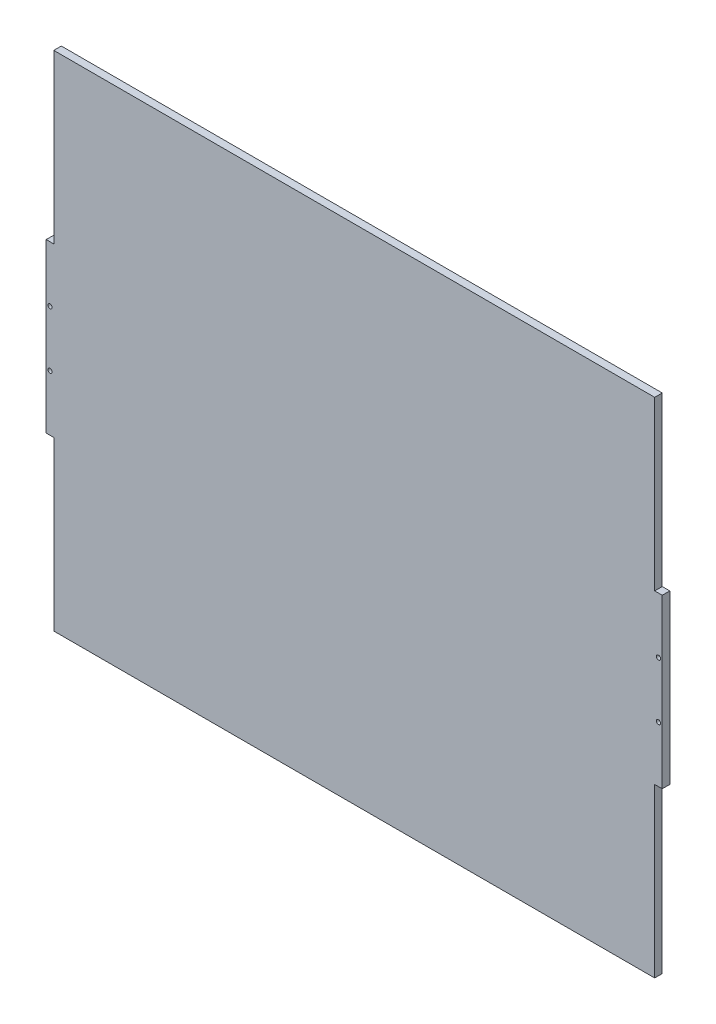
SolidWorks part; units mm, degrees
ref_plane "Front Plane" through (0, 0, 0) normal (0, 0, 1) x (1, 0, 0)
ref_plane "Top Plane" through (0, 0, 0) normal (0, 1, 0) x (1, 0, 0)
ref_plane "Right Plane" through (0, 0, 0) normal (1, 0, 0) x (0, 0, -1)
sketch "Sketch1" plane through (0, 0, 0) normal (0, 0, 1) x (1, 0, 0)
  line L1 (0, 0) -> (490, 0)
  line L2 (0, 0) -> (0, 400)
  line L3 (0, 400) -> (490, 400)
  line L4 (490, 0) -> (490, 400)
  dimension "D1" = 490
  dimension "D2" = 400
extrude "Boss-Extrude1" add sketch "Sketch1" along normal blind 6
sketch "Sketch2" plane through (0, 0, 6) normal (0, 0, 1) x (1, 0, 0)
  line L1 (490, 400) -> (484, 400)
  line L2 (490, 400) -> (490, 266.6667)
  line L3 (490, 266.6667) -> (484, 266.6667)
  line L4 (484, 400) -> (484, 266.6667)
  line L6 (0, 400) -> (6, 400)
  line L7 (0, 400) -> (0, 266.6667)
  line L8 (0, 266.6667) -> (6, 266.6667)
  line L9 (6, 400) -> (6, 266.6667)
  line L10 (0, 0) -> (6, 0)
  line L11 (0, 0) -> (0, 133.3333)
  line L12 (0, 133.3333) -> (6, 133.3333)
  line L13 (6, 0) -> (6, 133.3333)
  line L14 (490, 0) -> (484, 0)
  line L15 (490, 0) -> (490, 133.3333)
  line L16 (490, 133.3333) -> (484, 133.3333)
  line L17 (484, 0) -> (484, 133.3333)
  dimension "D1" = 6
  dimension "D2" = 133.3333
extrude "Cut-Extrude1" cut sketch "Sketch2" against normal blind 12
hole_wizard "M3 Clearance Hole1" positions "Sketch3" profile "Sketch4" hole size "M3" standard "ANSI Metric" end condition through all
sketch "Sketch3" plane through (0, 0, 6) normal (0, 0, 1) x (1, 0, 0)
  line L0 (0, 266.6667) -> (0, 133.3333) construction
  line L1 (0, 266.6667) -> (6, 266.6667) construction
  line L2 (6, 133.3333) -> (0, 133.3333) construction
  line L3 (490, 133.3333) -> (490, 266.6667) construction
  line L4 (484, 266.6667) -> (490, 266.6667) construction
  line L5 (490, 133.3333) -> (484, 133.3333) construction
  point P0 (3, 222.2233)
  point P7 (3, 177.7767)
  point P12 (487, 222.2233)
  point P14 (487, 177.7767)
  dimension "D1" = 3
  dimension "D2" = 44.4433
  dimension "D3" = 44.4433
  dimension "D4" = 3
  dimension "D5" = 3
  dimension "D6" = 44.4433
  dimension "D7" = 44.4433
sketch "Sketch4" plane through (3, 222.2233, 6) normal (1, 0, 0) x (0, -1, 0)
  line L0 (0, 0) -> (0, 6)
  line L1 (0, 6) -> (1.7, 6)
  line L2 (1.7, 6) -> (1.7, 0)
  line L5 (1.7, 0) -> (0, 0)
  line L11 (0, -6.35) -> (0, 107.95) construction
  dimension "Thru Hole Dia." = 3.4
  dimension "Thru Hole Depth" = 6
